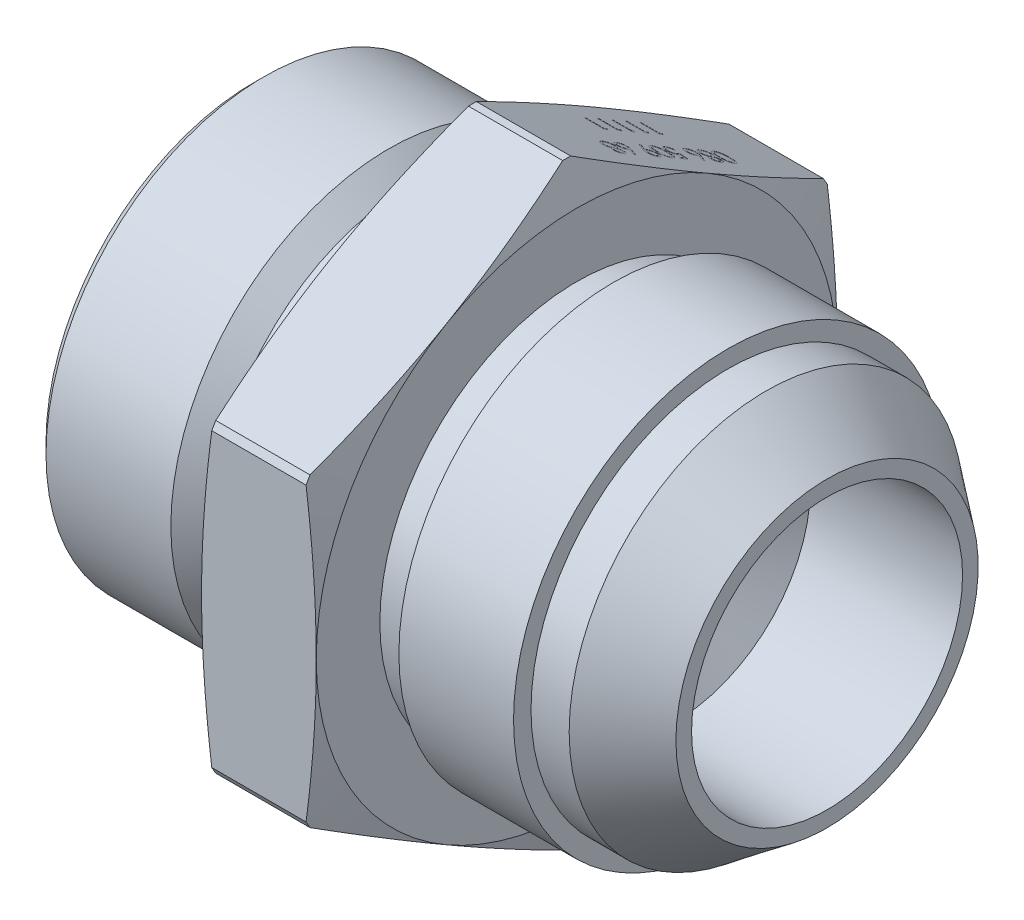
SolidWorks part; units mm, degrees
material "4140 H/T"
ref_plane "Front Plane" through (0, 0, 0) normal (0, 0, 1) x (1, 0, 0)
ref_plane "Top Plane" through (0, 0, 0) normal (0, 1, 0) x (1, 0, 0)
ref_plane "Right Plane" through (0, 0, 0) normal (1, 0, 0) x (0, 0, -1)
sketch "Sketch1" plane through (0, 0, 0) normal (0, 0, 1) x (1, 0, 0)
  line L0 (0, 0) -> (53.9967, 0) construction
  line L1 (0, 18.4) -> (0, 19.925)
  line L2 (0, 19.925) -> (1, 20.925)
  line L3 (1, 20.925) -> (12.975, 20.925)
  line L4 (55, 13) -> (40.4, 13)
  line L5 (20.978, 28.65) -> (30.022, 28.65)
  line L6 (31, 25) -> (31, 18.9)
  line L7 (31, 18.9) -> (34.5, 18.9)
  line L8 (34.5, 18.9) -> (34.5, 20.575)
  line L9 (34.5, 20.575) -> (45.5, 20.575)
  line L10 (45.5, 20.575) -> (45.5, 18.9)
  line L11 (45.5, 18.9) -> (49.161, 18.9)
  line L12 (49.161, 18.9) -> (55, 14.5)
  line L13 (55, 14.5) -> (55, 13)
  line L14 (35.5931, 5) -> (16.0086, 5)
  line L15 (15, 18.9) -> (12.975, 20.925)
  line L16 (20, 25) -> (20, 19.7)
  line L17 (40.4, 13) -> (35.5931, 5)
  line L18 (0, 18.4) -> (6, 15)
  line L19 (15, 18.9) -> (19.2, 18.9)
  line L20 (20.978, 28.65) -> (20, 25)
  line L21 (30.022, 28.65) -> (31, 25)
  line L22 (6, 15) -> (10, 15)
  line L23 (10, 15) -> (16.0086, 5)
  arc A0 (20, 19.7) -> (19.2, 18.9) centre (19.2, 19.7) cw
  dimension "D28" = 0.8
  dimension "D2" = 10
  dimension "D3" = 37.8
  dimension "D4" = 29
  dimension "D5" = 9.5
  dimension "D6" = 41.15
  dimension "D7" = 20.5
  dimension "D8" = 11
  dimension "D9" = 50
  dimension "D10" = 55
  dimension "D11" = 41.85
  dimension "D12" = 15
  dimension "D13" = 57.3
  dimension "D14" = 20
  dimension "D15" = 15
  dimension "D16" = 45
  dimension "D17" = 15
  dimension "D18" = 37.8
  dimension "D19" = 37
  dimension "D20" = 26
  dimension "D21" = 14.6
  dimension "D22" = 59
  dimension "D23" = 36.8
  dimension "D24" = 6
  dimension "D25" = 30
  dimension "D26" = 59
  dimension "D27" = 10
  dimension "D29" = 1
  dimension "D30" = 45
revolve "Revolve1" add sketch "Sketch1" angle 360 about L0
cosmetic thread "Cosmetic Thread1" parameters "D2"=38.9
cosmetic thread "Cosmetic Thread2" parameters "D2"=39.1
sketch "Sketch2" plane through (31, 0, 0) normal (1, 0, 0) x (0, 0, -1)
  line L1 (25, -14.4338) -> (25, 14.4338)
  line L2 (25, 14.4338) -> (0, 28.8675)
  line L3 (0, 28.8675) -> (-25, 14.4338)
  line L4 (-25, 14.4338) -> (-25, -14.4338)
  line L5 (-25, -14.4338) -> (0, -28.8675)
  line L6 (0, -28.8675) -> (25, -14.4338)
  circle A0 centre (0, 0) radius 25 construction
  dimension "D1" = 50
extrude "Extrude1" cut sketch "Sketch2" against normal up to surface (11 mm away) flip side to cut up to face at (20, 0, 19.7)
sketch "Sketch4" plane through (0, 21.6506, -12.5) normal (0, 0.866, -0.5) x (1, 0, 0)
  line L0 (26.6, 11.4801) -> (26.6, -12.1882) construction
  text T0 "086 509 68\r\n11111" font "Century Gothic" height 2
  dimension "D1" = 26.6
extrude "Cut-Extrude1" cut sketch "Sketch4" against normal blind 0.01
sketch "Sketch5" [suppressed] plane through (21.8, 0, 0) normal (-1, 0, 0) x (0, 0, 1)
  circle A0 centre (0, 0) radius 18.94
  circle A1 centre (0, 0) radius 25
  circle A2 centre (0, 0) radius 25
  circle A3 centre (0, 0) radius 18.94 construction
  dimension "D1" = 0
